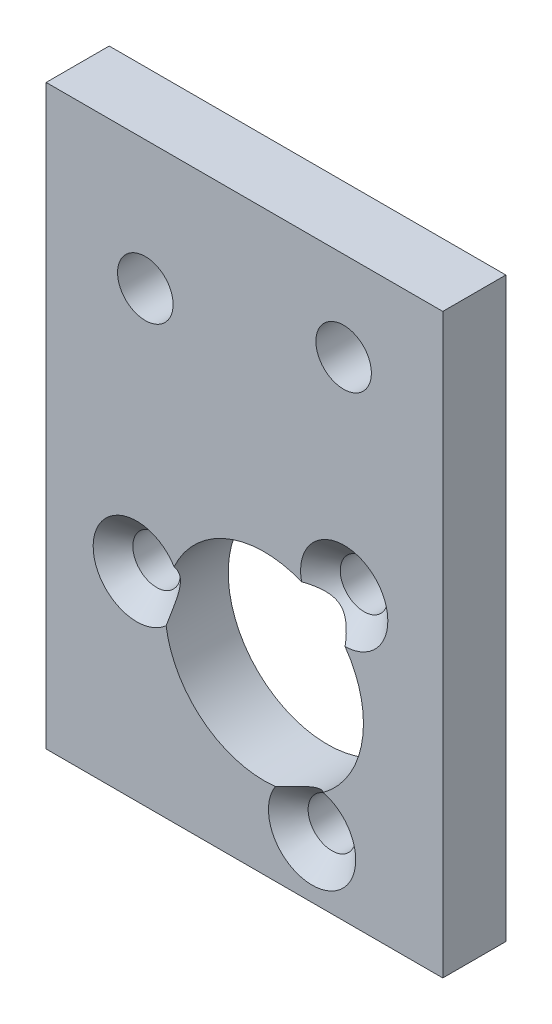
SolidWorks part; units mm, degrees
ref_plane "Front Plane" through (0, 0, 0) normal (0, 0, 1) x (1, 0, 0)
ref_plane "Top Plane" through (0, 0, 0) normal (0, 1, 0) x (1, 0, 0)
ref_plane "Right Plane" through (0, 0, 0) normal (1, 0, 0) x (0, 0, -1)
sketch "Sketch1" plane through (0, 0, 0) normal (0, 0, 1) x (1, 0, 0)
  line L1 (0, 0) -> (20, 0)
  line L2 (0, 0) -> (0, 29.11)
  line L3 (0, 29.11) -> (20, 29.11)
  line L4 (20, 0) -> (20, 29.11)
  circle A0 centre (5, 22.61) radius 1.4
  circle A1 centre (15, 24.61) radius 1.4
  arc A2 (15.0728, 12.0104) -> (12.8801, 13.743) centre (15.03, 14.21) ccw
  arc A3 (6.4499, 11.1828) -> (6.049, 8.4114) centre (4.57, 10.04) ccw
  arc A4 (11.5537, 4.1408) -> (13.9699, 5.0876) centre (13.41, 2.96) ccw
  circle A7 centre (15.03, 14.21) radius 1.2
  circle A8 centre (4.57, 10.04) radius 1.2
  circle A9 centre (13.41, 2.96) radius 1.2
  circle A10 centre (11, 9.11) radius 5
extrude "Boss-Extrude2" add sketch "Sketch1" against normal blind 3.18 contours A0 | A1 | L2 L1 L4 L3 | A7 | A10 | A8 | A9
hole_wizard "CSK for M2 Flat Head Machine Screw1" positions "Sketch10" profile "Sketch11" countersink size "M2" standard "ANSI Metric"
sketch "Sketch10" plane through (0, 0, 0) normal (0, 0, 1) x (1, 0, 0)
  point P0 (4.57, 10.04)
  point P3 (15.03, 14.21)
  point P6 (13.41, 2.96)
sketch "Sketch11" plane through (4.57, 10.04, 0) normal (1, 0, 0) x (0, -1, 0)
  line L0 (0, 0) -> (0, 4.23)
  line L1 (0, 4.23) -> (1.2, 3.509)
  line L2 (1.2, 3.509) -> (1.2, 1)
  line L3 (1.2, 1) -> (2.2, 0)
  line L5 (2.2, 0) -> (0, 0)
  line L6 (-1.2, 1) -> (-2.2, 0) construction
  line L10 (0, 4.23) -> (-1.2, 3.509) construction
  line L11 (0, -6.35) -> (0, 107.95) construction
  dimension "Hole Dia." = 2.4
  dimension "Hole Depth" = 4.23
  dimension "Near C'Sink Dia." = 4.4
  dimension "Near C'Sink Angle" = 90
  dimension "Drill Angle" = 118
